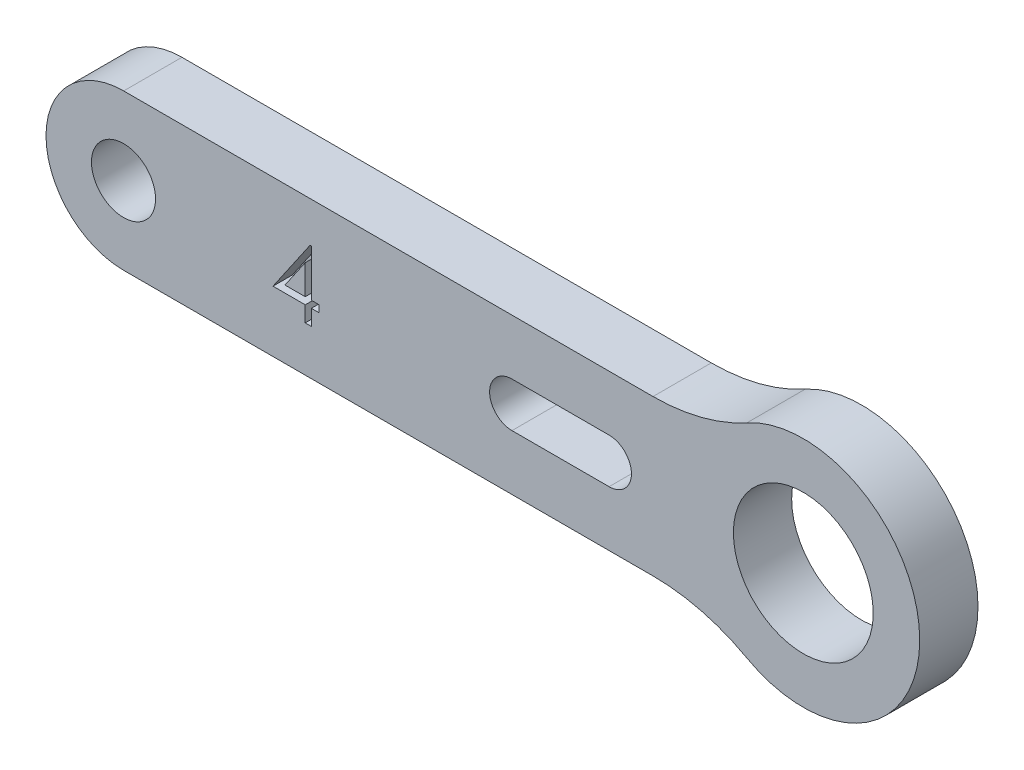
SolidWorks part; units mm, degrees
ref_plane "前视基准面" through (0, 0, 0) normal (0, 0, 1) x (1, 0, 0)
ref_plane "上视基准面" through (0, 0, 0) normal (0, 1, 0) x (1, 0, 0)
ref_plane "右视基准面" through (0, 0, 0) normal (1, 0, 0) x (0, 0, -1)
ref_plane "基准面4" through (0, 0, 3) normal (0, 0, 1) x (1, 0, 0)
sketch "草图1" plane through (0, 0, 3) normal (0, 0, 1) x (1, 0, 0)
  line L0 (15.6408, 8) -> (-11.611, 8)
  line L1 (-11.611, 0) -> (15.6462, 0)
  line L2 (13.3804, 2.8503) -> (8.3788, 2.8503)
  line L3 (8.3788, 5.1503) -> (13.3804, 5.1503)
  circle A0 centre (-11.6194, 4.0002) radius 1.65
  arc A1 (20.4784, 9.248) -> (15.6408, 8) centre (15.6408, 18) cw
  arc A2 (-11.611, 8) -> (-11.611, 0) centre (-11.611, 4) ccw
  arc A3 (15.6462, 0) -> (20.4804, -1.2461) centre (15.6462, -10) cw
  arc A4 (20.4804, -1.2461) -> (20.4784, 9.248) centre (23.3783, 4.0015) ccw
  circle A5 centre (23.3793, 4.0005) radius 3.6
  arc A6 (13.3804, 5.1503) -> (13.3804, 2.8503) centre (13.3804, 4.0003) cw
  arc A7 (8.3788, 2.8503) -> (8.3788, 5.1503) centre (8.3788, 4.0003) cw
extrude "凸台-拉伸1" add sketch "草图1" against normal blind 3
sketch "草图2" plane through (0, 0, 3) normal (0, 0, 1) x (1, 0, 0)
  text T0 "4"
extrude "切除-拉伸1" cut sketch "草图2" against normal blind 1
